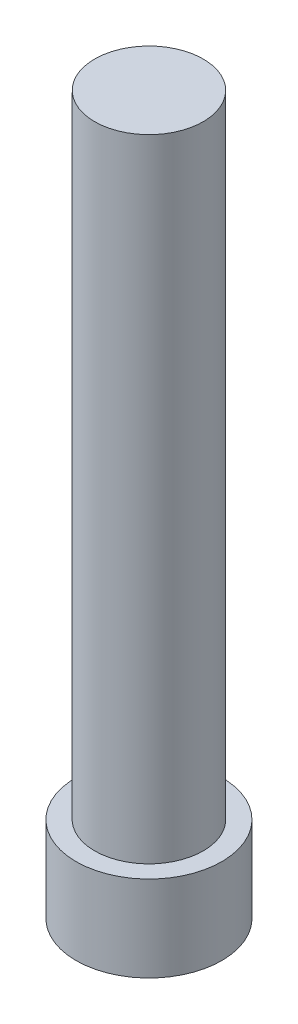
SolidWorks part; units mm, degrees
ref_plane "Front Plane" through (0, 0, 0) normal (0, 0, 1) x (1, 0, 0)
ref_plane "Top Plane" through (0, 0, 0) normal (0, 1, 0) x (1, 0, 0)
ref_plane "Right Plane" through (0, 0, 0) normal (1, 0, 0) x (0, 0, -1)
sketch "Sketch2" plane through (0, 0, 0) normal (0, 1, 0) x (1, 0, 0)
  circle A0 centre (0, 0) radius 2.55
  dimension "D1" = 5.1
extrude "Boss-Extrude1" add sketch "Sketch2" along normal blind 3
sketch "Sketch3" plane through (0, 3, 0) normal (0, 1, 0) x (1, 0, 0)
  circle A0 centre (0, 0) radius 1.9
  dimension "D1" = 3.8
extrude "Boss-Extrude2" add sketch "Sketch3" along normal blind 22.1
